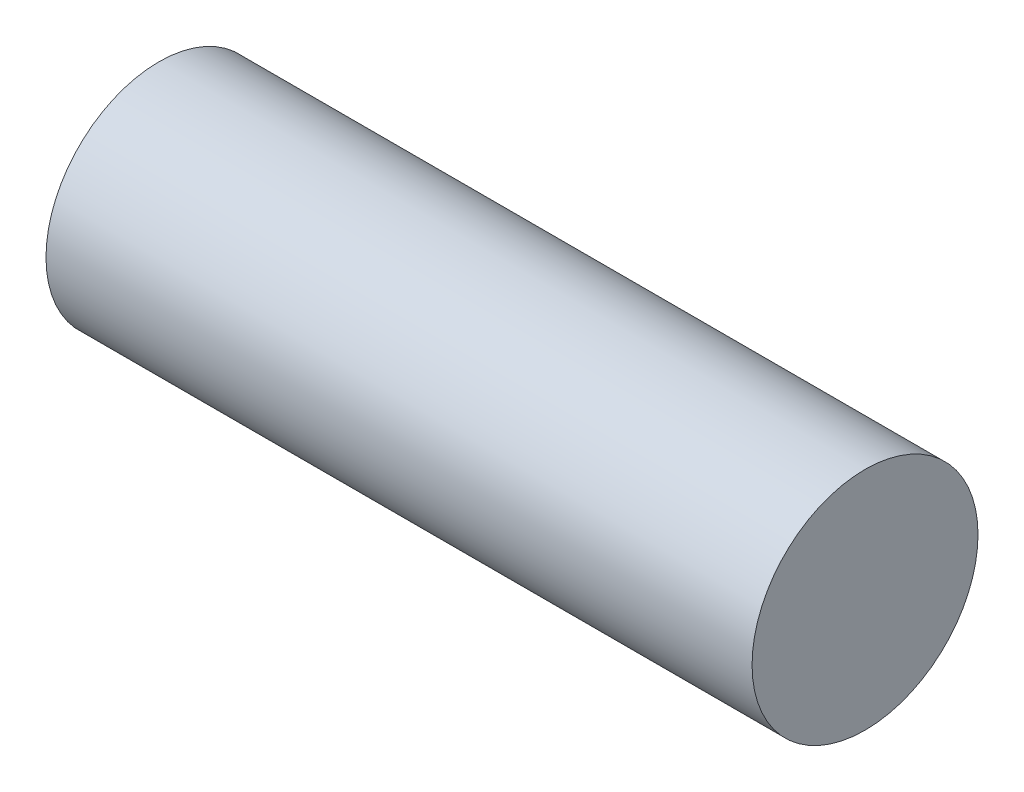
SolidWorks part; units mm, degrees
ref_plane "Front Plane" through (0, 0, 0) normal (1, 0, 0) x (0, 1, 0)
ref_plane "Top Plane" through (0, 0, 0) normal (0, 0, 1) x (0, 1, 0)
ref_plane "Right Plane" through (0, 0, 0) normal (0, 1, 0) x (-1, 0, 0)
sketch "Sketch1" plane through (0, 0, 0) normal (1, 0, 0) x (0, 1, 0)
  circle A0 centre (0, 0) radius 4
  dimension "D1" = 8
extrude "Boss-Extrude1" add sketch "Sketch1" along normal blind 25
